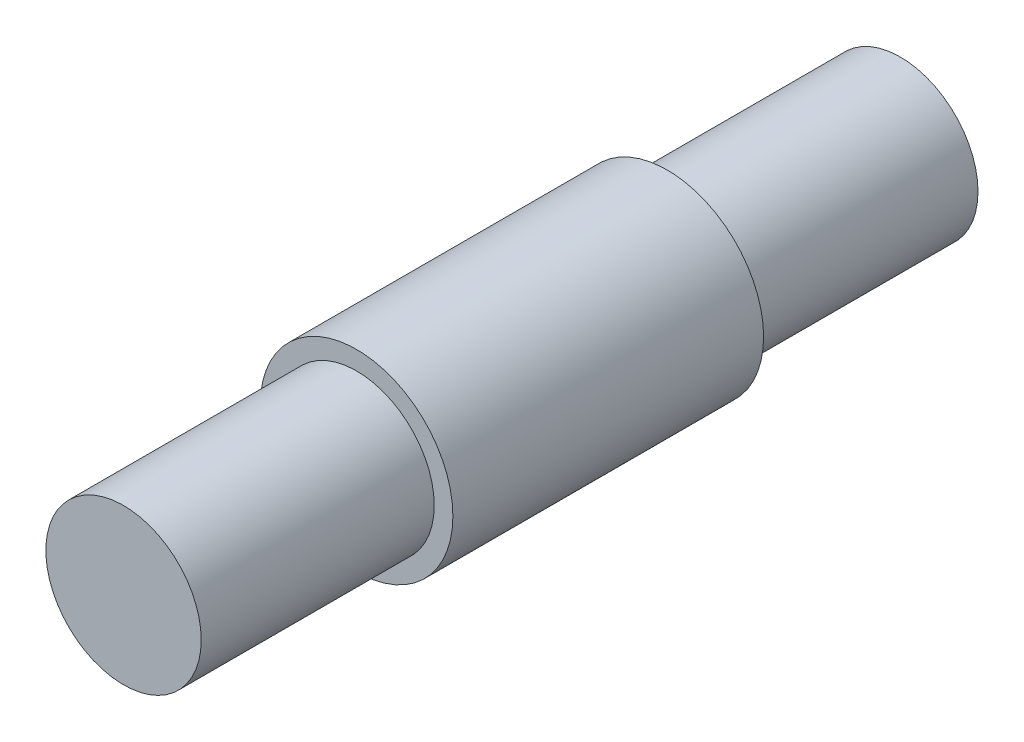
SolidWorks part; units mm, degrees
ref_plane "Front Plane" through (0, 0, 0) normal (0, 0, 1) x (1, 0, 0)
ref_plane "Top Plane" through (0, 0, 0) normal (0, 1, 0) x (1, 0, 0)
ref_plane "Right Plane" through (0, 0, 0) normal (1, 0, 0) x (0, 0, -1)
sketch "Sketch1" plane through (0, 0, 0) normal (0, 0, 1) x (1, 0, 0)
  circle A0 centre (0, 0) radius 3.937
  dimension "D1" = 7.874
extrude "Boss-Extrude1" add sketch "Sketch1" along normal blind 12.7
sketch "Sketch2" plane through (0, 0, 12.7) normal (0, 0, 1) x (1, 0, 0)
  circle A0 centre (0, 0) radius 3.175
  dimension "D1" = 6.35
extrude "Boss-Extrude2" add sketch "Sketch2" along normal blind 9.525 and the other way blind 22.225
